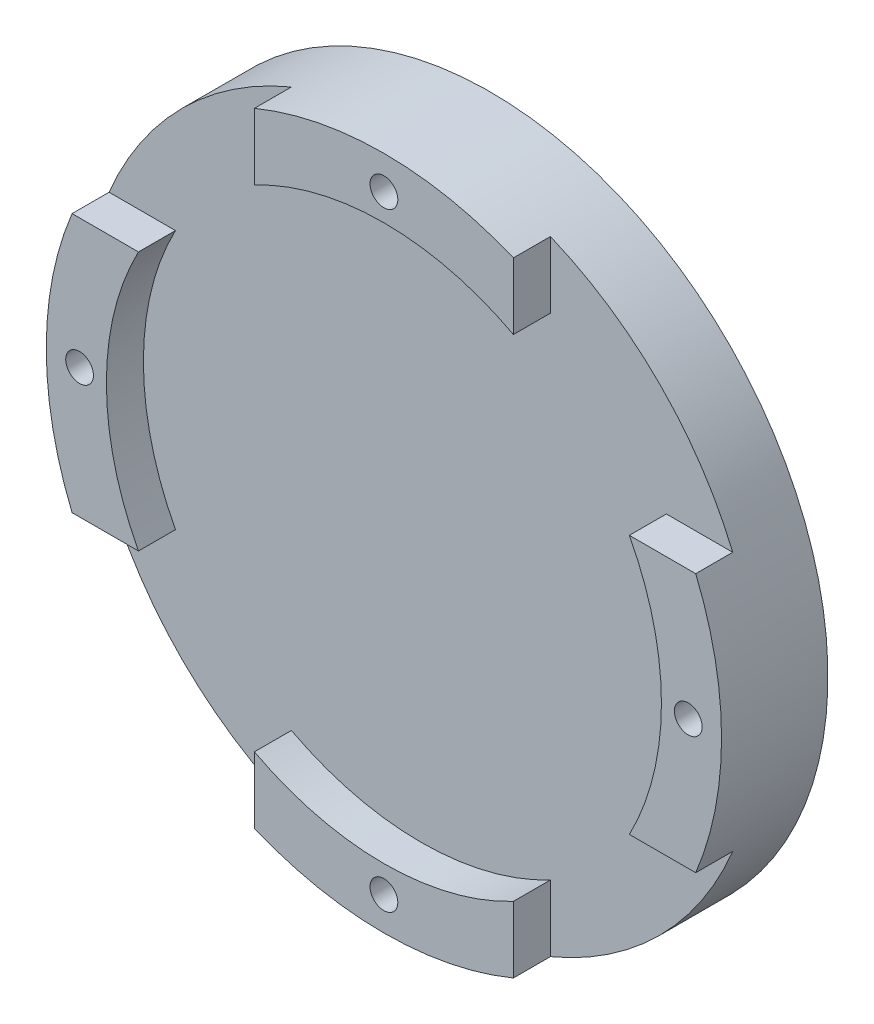
SolidWorks part; units mm, degrees
ref_plane "前视基准面" through (0, 0, 0) normal (0, 0, 1) x (1, 0, 0)
ref_plane "上视基准面" through (0, 0, 0) normal (0, 1, 0) x (1, 0, 0)
ref_plane "右视基准面" through (0, 0, 0) normal (1, 0, 0) x (0, 0, -1)
other "Configuration Table"
sketch "草图1" plane through (0, 0, 0) normal (0, 0, 1) x (1, 0, 0)
  circle A0 centre (0, 0) radius 36.5
  dimension "D1" = 73
extrude "凸台-拉伸1" add sketch "草图1" along normal blind 6.5
sketch "草图3" plane through (0, 0, 6.5) normal (0, 0, 1) x (1, 0, 0)
  line L0 (0, -30) -> (0, -36.5) construction
  line L1 (-14, -26.533) -> (-14, -33.7083)
  line L2 (14, -26.533) -> (14, -33.7083)
  line L3 (0, -30) -> (0, 0) construction
  line L4 (-14, -26.533) -> (14, -26.533) construction
  line L5 (-26.533, 14) -> (-33.7083, 14)
  line L6 (-26.533, -14) -> (-33.7083, -14)
  line L7 (14, 26.533) -> (14, 33.7083)
  line L8 (-14, 26.533) -> (-14, 33.7083)
  line L9 (26.533, -14) -> (33.7083, -14)
  line L10 (26.533, 14) -> (33.7083, 14)
  circle A0 centre (0, 0) radius 30
  circle A1 centre (0, 0) radius 36.5 construction
  arc A2 (-14, -26.533) -> (14, -26.533) centre (0, 0) ccw
  arc A3 (-14, -33.7083) -> (14, -33.7083) centre (0, 0) ccw
  circle A4 centre (0, 0) radius 30
  arc A5 (-33.7083, 14) -> (-33.7083, -14) centre (0, 0) ccw
  arc A6 (-26.533, 14) -> (-26.533, -14) centre (0, 0) ccw
  circle A7 centre (0, 0) radius 30
  arc A8 (14, 33.7083) -> (-14, 33.7083) centre (0, 0) ccw
  arc A9 (14, 26.533) -> (-14, 26.533) centre (0, 0) ccw
  circle A10 centre (0, 0) radius 30
  arc A11 (33.7083, -14) -> (33.7083, 14) centre (0, 0) ccw
  arc A12 (26.533, -14) -> (26.533, 14) centre (0, 0) ccw
  arc A13 (-33.7083, -14) -> (-14, -33.7083) centre (0, 0) ccw
  arc A14 (14, 33.7083) -> (33.7083, 14) centre (0, 0) cw
  arc A15 (33.7083, -14) -> (14, -33.7083) centre (0, 0) cw
  arc A16 (-14, 33.7083) -> (-33.7083, 14) centre (0, 0) ccw
  arc A17 (-14, 26.533) -> (-26.533, 14) centre (0, 0) ccw
  arc A18 (14, 26.533) -> (26.533, 14) centre (0, 0) cw
  arc A19 (26.533, -14) -> (14, -26.533) centre (0, 0) cw
  arc A20 (-26.533, -14) -> (-14, -26.533) centre (0, 0) ccw
  point P32 (0, 0)
  circle M4 centre (0, 0) radius 36.5
  dimension "D1" = 60
  dimension "D2" = 28
  dimension "D3" = 4
extrude "切除-拉伸2" cut sketch "草图3" against normal blind 4 contours A0 L10 L7 M4 | A0 L2 L9 M4 | A0 L6 L1 M4 | A0 L8 L5 M4
sketch "草图4" plane through (0, 0, 6.5) normal (0, 0, 1) x (1, 0, 0)
  circle A0 centre (0, 0) radius 30
  arc M2 (-14, 26.533) -> (-26.533, 14) centre (0, 0) ccw
  arc M6 (-26.533, -14) -> (-14, -26.533) centre (0, 0) ccw
  arc M10 (14, -26.533) -> (26.533, -14) centre (0, 0) ccw
  arc M14 (26.533, 14) -> (14, 26.533) centre (0, 0) ccw
  dimension "D1" = 60
extrude "切除-拉伸3" cut sketch "草图4" against normal blind 4 contours A0 M14 M2 M6 M10
sketch "草图6" plane through (0, 0, 0) normal (0, 0, -1) x (-1, 0, 0)
  line L0 (0, 0) -> (-32.9, 0) construction
  circle A0 centre (0, 0) radius 32.9 construction
  circle A1 centre (0, 32.9) radius 1.5
  circle A2 centre (32.9, 0) radius 1.5
  circle A3 centre (0, -32.9) radius 1.5
  circle A4 centre (-32.9, 0) radius 1.5
  point P14 (0, 0)
  dimension "D1" = 65.8
  dimension "D2" = 3
  dimension "D4" = 32.9
  dimension "D3" = 4
extrude "切除-拉伸5" cut sketch "草图6" against normal through all contours A2 | A3 | A1 | A4
sketch "草图7" plane through (0, 0, 0) normal (0, 0, -1) x (-1, 0, 0)
  circle A1 centre (0, 0) radius 36.5
  circle M1 centre (32.9, 0) radius 1.5
  circle M2 centre (0, -32.9) radius 1.5
  circle M3 centre (0, 32.9) radius 1.5
  circle M4 centre (-32.9, 0) radius 1.5
  circle M5 centre (0, 0) radius 36.5
  dimension "D1" = 73
extrude "凸台-拉伸2" add sketch "草图7" along normal blind 5 contours M5 M2 M4 M3 M1
sketch "草图8" plane through (0, 0, -5) normal (0, 0, -1) x (-1, 0, 0)
  circle A0 centre (0, 0) radius 31.2
  dimension "D1" = 62.4
extrude "切除-拉伸6" cut sketch "草图8" against normal blind 5 contours A0
sketch "草图9" plane through (0, 0, 0) normal (0, 0, -1) x (-1, 0, 0)
  circle A0 centre (0, 0) radius 3.5
  dimension "D1" = 7
extrude "凸台-拉伸3" add sketch "草图9" along normal blind 8
